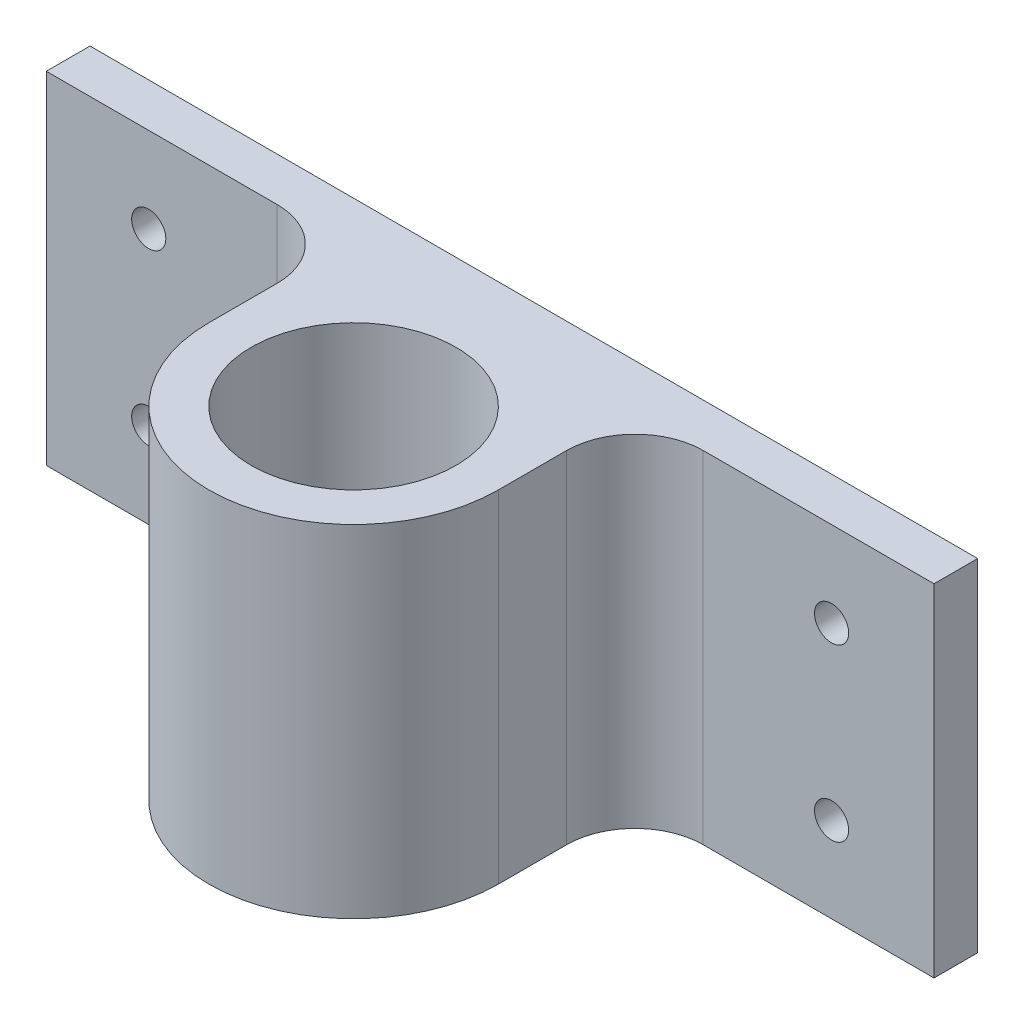
SolidWorks part; units mm, degrees
ref_plane "Front Plane" through (0, 0, 0) normal (0, 0, 1) x (1, 0, 0)
ref_plane "Top Plane" through (0, 0, 0) normal (0, 1, 0) x (1, 0, 0)
ref_plane "Right Plane" through (0, 0, 0) normal (1, 0, 0) x (0, 0, -1)
sketch "Sketch1" plane through (0, 0, 0) normal (0, 1, 0) x (1, 0, 0)
  line L0 (0, 208.5321) -> (0, -229.5844) construction
  line L1 (-372.5532, 0) -> (349.4855, 0) construction
  line L2 (-325, 132) -> (325, 132)
  line L3 (-325, 132) -> (-325, 100)
  line L4 (325, 132) -> (325, 100)
  line L5 (-325, 100) -> (-156, 100)
  line L6 (-106, 0) -> (-106, 50)
  line L7 (156, 100) -> (325, 100)
  line L8 (106, 0) -> (106, 50)
  circle A0 centre (0, 0) radius 75
  arc A1 (-106, 0) -> (106, 0) centre (0, 0) ccw
  arc A2 (-106, 50) -> (-156, 100) centre (-156, 50) ccw
  arc A3 (106, 50) -> (156, 100) centre (156, 50) cw
  point P10 (0, 132)
  dimension "D1" = 150
  dimension "D2" = 212
  dimension "D6" = 50
  dimension "D3" = 132
  dimension "D4" = 325
  dimension "D5" = 32
extrude "Boss-Extrude1" add sketch "Sketch1" along normal blind 250
sketch "Sketch2" plane through (0, 0, -132) normal (0, 0, -1) x (-1, 0, 0)
  line L0 (0, 270.0341) -> (0, -41.1044) construction
  line L1 (-325, 250) -> (325, 250) construction
  line L2 (-325, 0) -> (325, 0) construction
  circle A0 centre (-250, 187.5) radius 12.5
  circle A1 centre (-250, 62.5) radius 12.5
  circle A2 centre (250, 62.5) radius 12.5
  circle A3 centre (250, 187.5) radius 12.5
  point P11 (0, 0)
  dimension "D1" = 25
  dimension "D2" = 125
  dimension "D3" = 62.5
  dimension "D4" = 62.5
  dimension "D5" = 250
extrude "Cut-Extrude1" cut sketch "Sketch2" against normal blind 250
